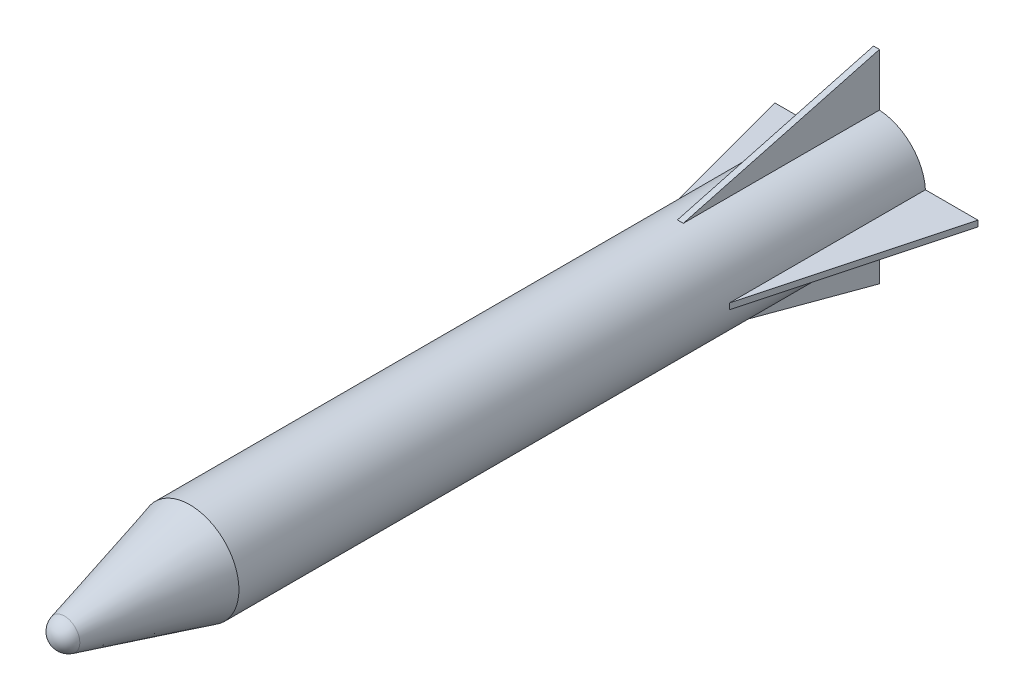
SolidWorks part; units mm, degrees
ref_plane "Front Plane" through (0, 0, 0) normal (1, 0, 0) x (0, 1, 0)
ref_plane "Top Plane" through (0, 0, 0) normal (0, 0, 1) x (0, 1, 0)
ref_plane "Right Plane" through (0, 0, 0) normal (0, 1, 0) x (-1, 0, 0)
sketch "Sketch1" plane through (0, 0, 0) normal (1, 0, 0) x (0, 1, 0)
  line L0 (0, 0) -> (0, 49.8162) construction
  line L1 (-9.5, 0) -> (-12.5, 0)
  line L2 (-9.5, 0) -> (-9.5, 70)
  line L4 (-12.5, 0) -> (-12.5, 175)
  line L5 (-9.5, 174.605) -> (-1.3943, 204.8559)
  line L7 (-3.9298, 206.9846) -> (-12.5, 175)
  line L8 (-12.5, 87.5) -> (-9.5, 87.5) construction
  line L9 (-8.2149, 190.9923) -> (-5.3171, 190.2158) construction
  line L10 (0, 206.9846) -> (0, 210)
  line L11 (-9.5, 70) -> (0, 79.5)
  line L12 (0, 79.5) -> (0, 80.5)
  line L13 (0, 80.5) -> (-9.5, 80.5)
  line L20 (-9.5, 80.5) -> (-9.5, 174.605)
  arc A0 (-3.9298, 206.9846) -> (0, 210) centre (0, 205.9316) cw
  arc A1 (-1.3943, 204.8559) -> (0, 206.9846) centre (2.5354, 203.8029) cw
  point P15 (-12.5, 87.5)
  dimension "D1" = 9.5
  dimension "D2" = 3
  dimension "D3" = 175
  dimension "D4" = 15
  dimension "D6" = 45
  dimension "D7" = 1
  dimension "D8" = 70
revolve "Revolve1" add sketch "Sketch1" angle 360 about L0
ref_plane "Plane2" through (33, 0, 0) normal (1, 0, 0) x (0, 1, 0)
sketch "Sketch5" plane through (33, 0, 0) normal (1, 0, 0) x (0, 1, 0)
  line L0 (0, 0) -> (-0.75, 0)
  line L1 (-12.5, 0) -> (12.5, 0) construction
  line L2 (-0.75, 0) -> (-0.75, 50)
  line L3 (-0.75, 50) -> (0.75, 50)
  line L4 (0.75, 50) -> (0.75, 0)
  line L5 (0.75, 0) -> (0, 0)
  dimension "D1" = 1.5
  dimension "D2" = 50
extrude "Boss-Extrude4" add sketch "Sketch5" against normal up to next
sketch "Sketch6" plane through (0, 0.75, 0) normal (0, 1, 0) x (-1, 0, 0)
  line L0 (-12.4775, 50) -> (-25.8749, 0)
  line L1 (-12.4775, 0) -> (-33, 0) construction
  line L2 (-25.8749, 0) -> (-33, 0)
  line L3 (-33, 13.75) -> (-33, -13.75) construction
  line L4 (-33, 0) -> (-33, 50)
  line L5 (-12.4775, 50) -> (-33, 50) construction
  line L6 (-33, 50) -> (-12.4775, 50)
  dimension "D1" = 75
extrude "Cut-Extrude1" cut sketch "Sketch6" against normal up to next contours L6 L0 L2 L4
pattern_circular "CirPattern9" count 4 over 360 about axis through (0, 0, 0) along (0, 0, 1) of "Boss-Extrude4", "Cut-Extrude1"
